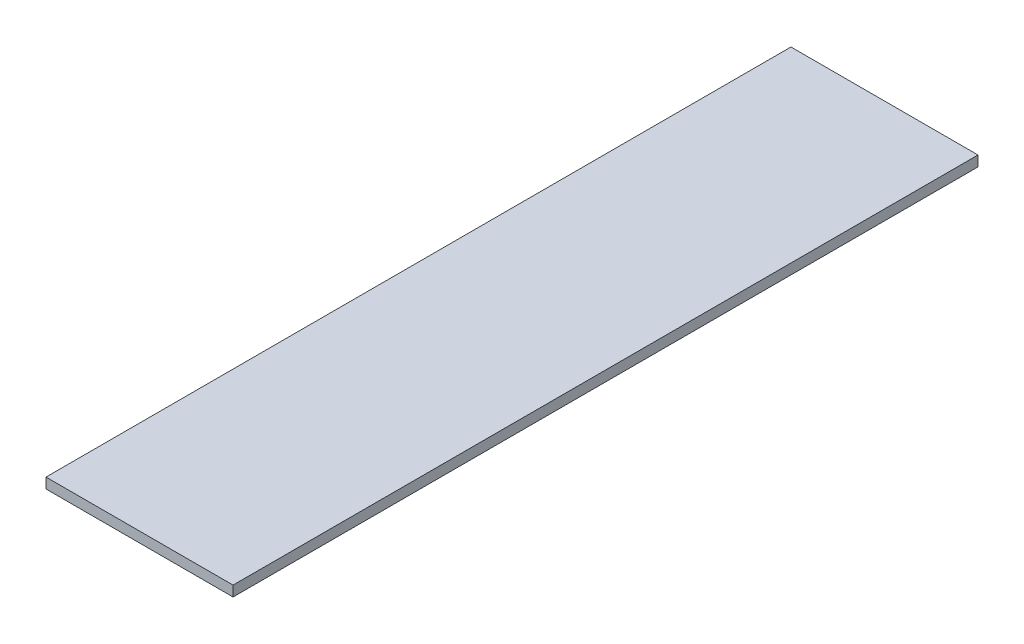
SolidWorks part; units mm, degrees
ref_plane "Front Plane" through (0, 0, 0) normal (0, 0, 1) x (1, 0, 0)
ref_plane "Top Plane" through (0, 0, 0) normal (0, 1, 0) x (1, 0, 0)
ref_plane "Right Plane" through (0, 0, 0) normal (1, 0, 0) x (0, 0, -1)
sketch "Sketch1" plane through (0, 0, 0) normal (0, 1, 0) x (1, 0, 0)
  line L1 (0, 0) -> (57.404, 0)
  line L2 (0, 0) -> (0, 228.6)
  line L3 (0, 228.6) -> (57.404, 228.6)
  line L4 (57.404, 0) -> (57.404, 228.6)
  dimension "D1" = 228.6
  dimension "D2" = 57.404
extrude "Base extrude" add sketch "Sketch1" along normal blind 3.175 contours L2 L3 L4 L1
